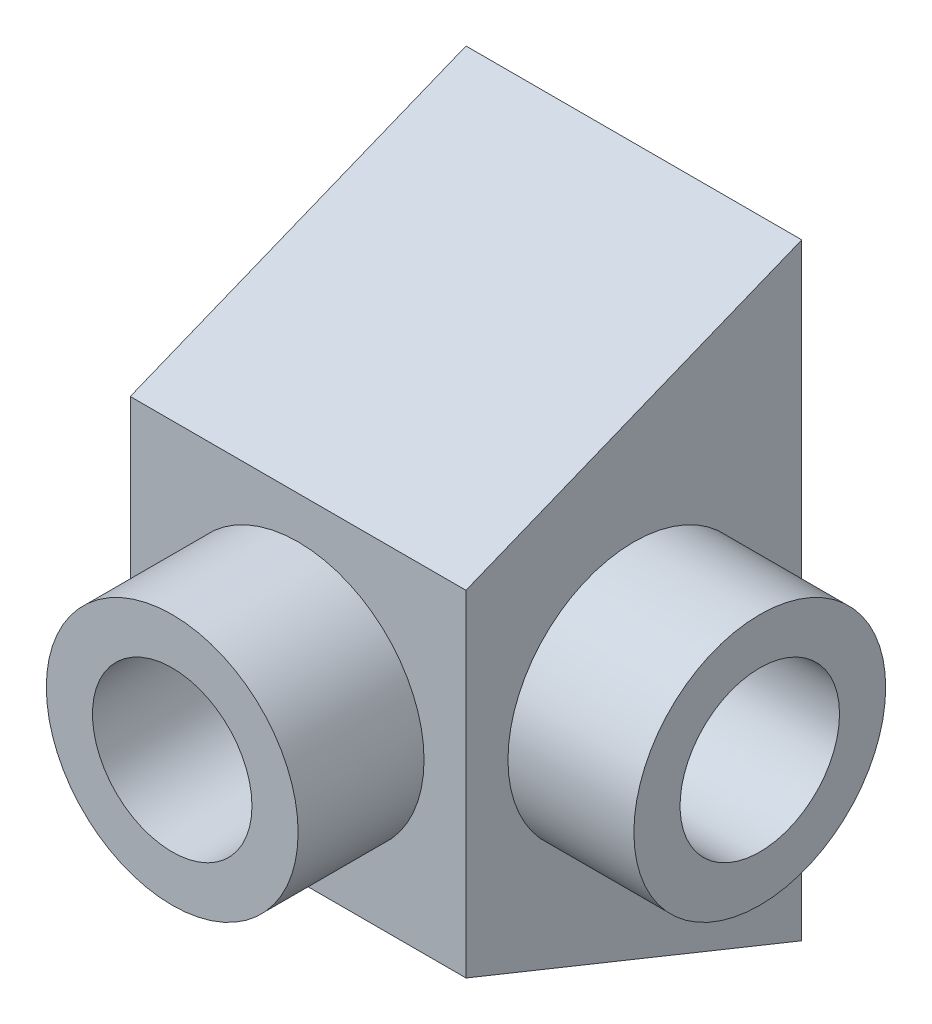
SolidWorks part; units mm, degrees
ref_plane "Alzado" through (0, 0, 0) normal (0, 0, 1) x (1, 0, 0)
ref_plane "Planta" through (0, 0, 0) normal (0, 1, 0) x (1, 0, 0)
ref_plane "Vista lateral" through (0, 0, 0) normal (1, 0, 0) x (0, 0, -1)
sketch "Croquis1" plane through (0, 0, 0) normal (0, 0, 1) x (1, 0, 0)
  circle A1 centre (0, 0) radius 19
  circle A2 centre (0, 0) radius 30
extrude "Saliente-Extruir1" add sketch "Croquis1" along normal blind 30
sketch "Croquis2" plane through (0, 0, 0) normal (0, 0, 1) x (1, 0, 0)
  line L1 (40, 40) -> (-40, 40)
  line L2 (40, 40) -> (40, -40)
  line L3 (40, -40) -> (-40, -40)
  line L4 (-40, 40) -> (-40, -40)
  point P0 (0, 0)
extrude "Saliente-Extruir2" add sketch "Croquis2" against normal blind 80
ref_plane "Plano1" through (40, 0, 0) normal (1, 0, 0) x (0, 0, -1)
sketch "Croquis3" plane through (40, 0, 0) normal (1, 0, 0) x (0, 0, -1)
  line L0 (0, 40) -> (0, -40) construction
  line L1 (0, -40) -> (80, -40) construction
  circle A0 centre (40, 0) radius 19
  circle A1 centre (40, 0) radius 30
extrude "Saliente-Extruir3" add sketch "Croquis3" along normal blind 30
ref_plane "Plano3" through (-40, 0, 0) normal (1, 0, 0) x (0, 0, -1)
sketch "Croquis4" plane through (-40, 0, 0) normal (1, 0, 0) x (0, 0, -1)
  line L0 (80, 40) -> (80, 72.32)
  line L1 (80, 72.32) -> (0, 40)
  line L2 (0, 40) -> (80, 40)
  line L3 (0, -40) -> (80, -40)
  line L4 (80, -40) -> (0, -40) construction
  line L5 (80, -40) -> (80, -72.32)
  line L6 (80, -72.32) -> (0, -40)
extrude "Saliente-Extruir4" add sketch "Croquis4" along normal blind 80
